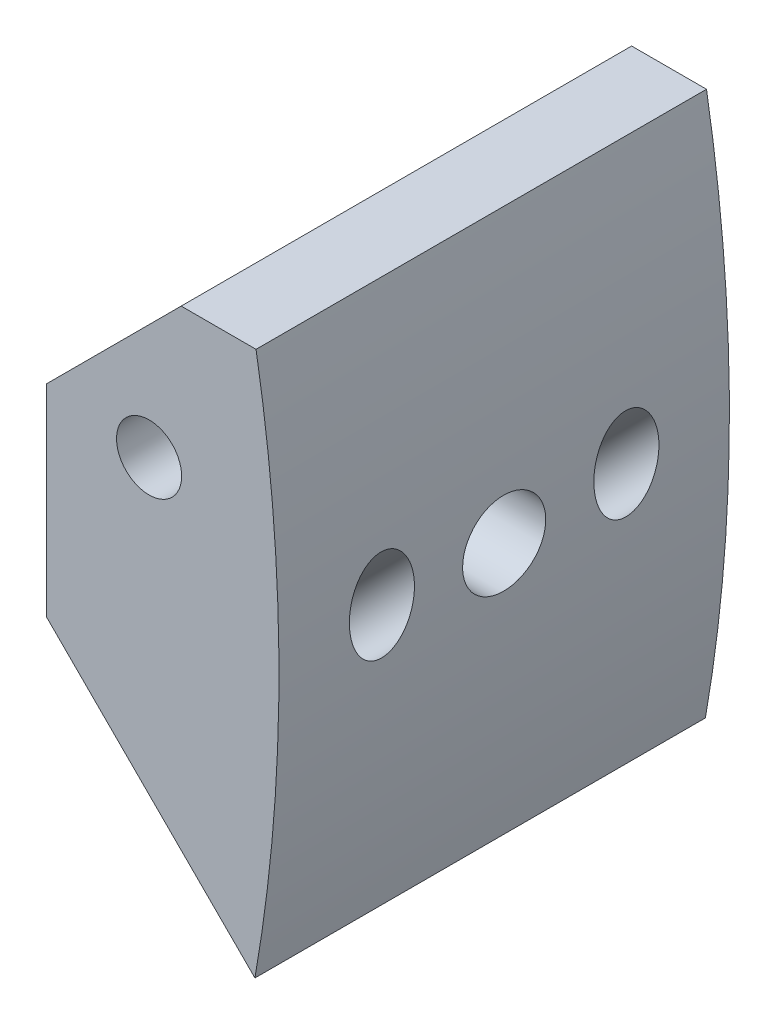
SolidWorks part; units mm, degrees
material "6061-T6 (SS)"
ref_plane "Front Plane" through (0, 0, 0) normal (0, 0, 1) x (1, 0, 0)
ref_plane "Top Plane" through (0, 0, 0) normal (0, 1, 0) x (1, 0, 0)
ref_plane "Right Plane" through (0, 0, 0) normal (1, 0, 0) x (0, 0, -1)
sketch "Sketch1" plane through (0, 0, 0) normal (0, 0, 1) x (1, 0, 0)
  line L0 (0, 0) -> (0, -13.1746)
  line L1 (0, -13.1746) -> (15.3242, -28.4988)
  line L2 (0, -6.5873) -> (15.3242, -6.5873) construction
  line L3 (15.3242, 15.3242) -> (0, 0) construction
  line L4 (15.3242, 15.3242) -> (15.3242, -6.5873) construction
  line L5 (15.3242, -6.5873) -> (15.3242, -28.4988) construction
  line L6 (19.05, -6.5873) -> (0, -6.5873) construction
  line L7 (0, 0) -> (0, 15.3242)
  line L8 (0, 15.3242) -> (15.3242, 15.3242)
  arc A0 (15.3242, 15.3242) -> (15.3242, -28.4988) centre (-47.244, -6.5873) cw
  dimension "D1" = 66.294
  dimension "D3" = 19.05
  dimension "D2" = 135
  dimension "D4" = 15.3242
extrude "Extrude1" add sketch "Sketch1" along normal blind 18.7198
sketch "Sketch23" plane through (0, 0, 0) normal (-1, 0, 0) x (0, 0, 1)
  line L0 (0, 0) -> (18.7198, 0) construction
  line L1 (18.7198, 15.3242) -> (18.7198, -13.1746) construction
  line L2 (9.3599, 0) -> (9.3599, -13.1746) construction
  line L3 (18.7198, -13.1746) -> (0, -13.1746) construction
  point P9 (9.3599, -6.5873)
sketch "Sketch2" plane through (0, 0, 0) normal (-1, 0, 0) x (0, 0, 1)
  line L0 (0, -6.5657) -> (18.7198, -6.5657) construction
  line L3 (9.3599, -13.1746) -> (9.3599, -6.5657) construction
  line L4 (18.7198, -13.1746) -> (0, -13.1746) construction
  point P6 (9.3599, -6.5657)
  dimension "D1" = 6.6089
sketch "Sketch13" plane through (0, 0, 18.7198) normal (0, 0, 1) x (1, 0, 0)
  line L0 (0, -13.1746) -> (0, 4.6054) construction
  line L1 (0, 4.6054) -> (30.3361, 4.6054)
  line L2 (0, 4.6054) -> (0, 31.0448)
  line L3 (0, 31.0448) -> (30.3361, 31.0448)
  line L4 (30.3361, 4.6054) -> (30.3361, 31.0448)
  dimension "D1" = 26.4394
  dimension "D2" = 30.3361
  dimension "D3" = 17.78
extrude "Extrude2" cut sketch "Sketch13" against normal through all
sketch "Sketch7" plane through (0, 0, 18.7198) normal (0, 0, 1) x (1, 0, 0)
  line L5 (19.05, -6.5873) -> (13.6525, -6.5873) construction
  line L6 (13.6525, -6.5873) -> (13.6525, -1.5073) construction
  arc A5 (15.3242, -28.4988) -> (18.0983, 4.6054) centre (-47.244, -6.5873) ccw construction
  dimension "D2" = 5.3975
  dimension "D4" = 5.08
hole_wizard "#6-32 Tapped Hole2" positions "Sketch9" profile "Sketch8" tap size "#6-32" standard "Ansi Inch" end condition through all
sketch "Sketch9" plane through (0, 0, 18.7198) normal (0, 0, 1) x (1, 0, 0)
  point P11 (13.6525, -1.5073)
sketch "Sketch8" plane through (13.6525, -1.5073, 18.7198) normal (1, 0, 0) x (0, -1, 0)
  line L0 (0, 0) -> (0, 18.7198)
  line L1 (0, 18.7198) -> (1.3525, 18.7198)
  line L2 (1.3525, 18.7198) -> (1.3525, 0)
  line L5 (1.3525, 0) -> (0, 0)
  line L11 (0, -6.35) -> (0, 107.95) construction
  dimension "Thru Tap Drill Dia." = 2.7051
  dimension "Thru Tap Drill Depth" = 18.7198
cosmetic thread "Hole Thread4" parameters "D2"=3.5052
sketch "Sketch10" plane through (-6.5873, -6.5873, 0) normal (-0.7071, -0.7071, 0) x (0.7071, -0.7071, 0)
  line L0 (30.9875, 9.3599) -> (18.5415, 9.3599) construction
  line L2 (18.5415, 9.3599) -> (18.5415, 16.9799) construction
  line L3 (18.5415, 9.3599) -> (18.5415, 1.7399) construction
  line L5 (30.9875, 18.7198) -> (30.9875, 0) construction
  dimension "D1" = 7.62
  dimension "D2" = 12.446
sketch "Sketch14" plane through (0, 0, 18.7198) normal (0, 0, 1) x (1, 0, 0)
  line L0 (0.6847, -13.8593) -> (7.2762, -7.2678)
  line L1 (0, -13.1746) -> (15.3242, -28.4988) construction
  line L2 (7.2762, -7.2678) -> (18.0525, -18.0441)
  line L3 (21.9157, -21.9073) -> (15.3242, -28.4988)
  line L4 (15.3242, -28.4988) -> (0.6847, -13.8593)
  line L5 (18.0525, -18.0441) -> (21.9157, -21.9073)
  arc A0 (15.3242, -28.4988) -> (18.0983, 4.6054) centre (-47.244, -6.5873) ccw construction
  dimension "D2" = 9.3218
  dimension "D3" = 15.24
extrude "Extrude3" cut sketch "Sketch14" against normal through all
sketch "Sketch16" plane through (0.0042, 0.0042, 0) normal (-0.7071, -0.7071, 0) x (0, 0, 1)
  line L2 (9.3599, -17.8863) -> (14.4399, -17.8863) construction
  line L3 (9.3599, -17.8863) -> (4.2799, -17.8863) construction
  line L4 (9.3599, -25.5242) -> (9.3599, -17.8863) construction
  line L5 (18.7198, -25.5242) -> (0, -25.5242) construction
  dimension "D1" = 10.16
  dimension "D3" = 7.6379
hole_wizard "#6-32 Tapped Hole1" positions "3DSketch1" profile "Sketch17" tap size "#6-32" standard "Ansi Inch" end condition through all
sketch3d "3DSketch1"
  point P0 (12.6517, -12.6433, 14.4399)
  point P8 (12.6517, -12.6433, 4.2799)
sketch "Sketch17" plane through (12.6517, -12.6433, 14.4399) normal (0, 0, 1) x (0.7071, -0.7071, 0)
  line L0 (0, 0) -> (0, 16.7209)
  line L1 (0, 16.7209) -> (1.3525, 16.7209)
  line L2 (1.3525, 16.7209) -> (1.3525, 0)
  line L5 (1.3525, 0) -> (0, 0)
  line L11 (0, -6.35) -> (0, 107.95) construction
  dimension "Thru Tap Drill Dia." = 2.7051
  dimension "Thru Tap Drill Depth" = 16.7209
cosmetic thread "Hole Thread1" parameters "D2"=3.5052
cosmetic thread "Hole Thread2" parameters "D2"=3.5052
hole_wizard "#8-32 Tapped Hole5" positions "Sketch26" profile "Sketch25" tap size "#8-32" standard "Ansi Inch"
sketch "Sketch26" plane through (0, 0, 0) normal (-1, 0, 0) x (0, 0, 1)
  point P1 (9.3599, -6.5873)
sketch "Sketch25" plane through (0, -6.5873, 9.3599) normal (0, 1, 0) x (0, 0, 1)
  line L0 (0, 0) -> (0, 20.0878)
  line L1 (0, 20.0878) -> (1.7272, 19.05)
  line L2 (1.7272, 19.05) -> (1.7272, 0)
  line L5 (1.7272, 0) -> (0, 0)
  line L10 (0, 20.0878) -> (-1.7272, 19.05) construction
  line L11 (0, -6.35) -> (0, 107.95) construction
  dimension "Tap Drill Dia." = 3.4544
  dimension "Tap Drill Depth" = 19.05
  dimension "Drill Angle" = 118
cosmetic thread "Hole Thread3" parameters "D1"=8.382, "D2"=4.1656
sketch "Sketch22" plane through (0, 0, 18.7198) normal (0, 0, 1) x (1, 0, 0)
  line L1 (0, 4.6054) -> (9.398, 4.6054)
  line L2 (0, 4.6054) -> (0, -17.0846)
  line L3 (0, -17.0846) -> (9.398, -17.0846)
  line L4 (9.398, 4.6054) -> (9.398, -17.0846)
  dimension "D1" = 21.6901
  dimension "D2" = 9.398
extrude "Extrude4" cut sketch "Sketch22" against normal through all
chamfer "Chamfer1" distance 5.588 angle 45 1 edges at (9.398, 4.6054, 9.3599)
